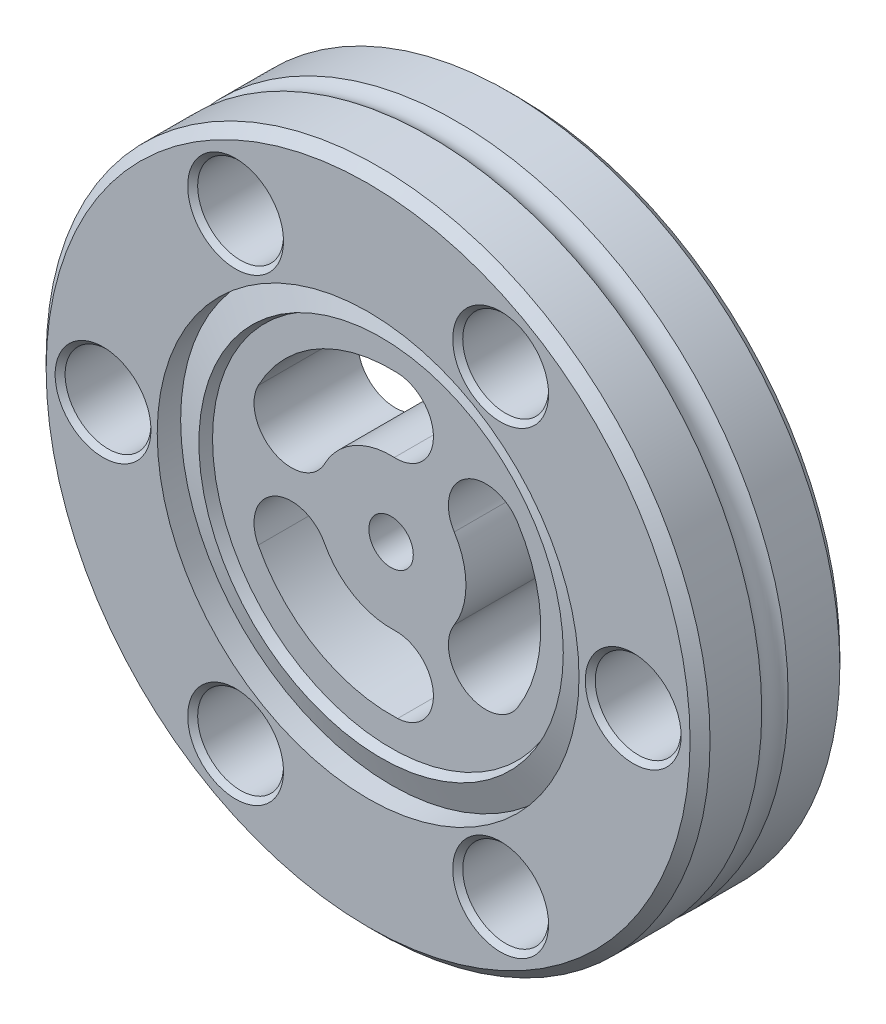
SolidWorks part; units mm, degrees
material "AISI 304"
ref_plane "Front Plane" through (0, 0, 0) normal (0, 0, 1) x (1, 0, 0)
ref_plane "Top Plane" through (0, 0, 0) normal (0, 1, 0) x (1, 0, 0)
ref_plane "Right Plane" through (0, 0, 0) normal (1, 0, 0) x (0, 0, -1)
sketch "Sketch1" plane through (0, 0, 0) normal (0, 1, 0) x (1, 0, 0)
  line L0 (9.0861, 2.6416) -> (0, 2.6416)
  line L1 (0, 2.6416) -> (0, -2.6416)
  line L2 (0, -2.6416) -> (9.0861, -2.6416)
  line L3 (9.0861, -2.6416) -> (9.271, -3.1496)
  line L4 (9.271, -3.1496) -> (10.7315, -2.618)
  line L5 (10.7315, -2.618) -> (10.7315, -3.81)
  line L6 (10.7315, -3.81) -> (16.891, -3.81)
  line L7 (16.891, -3.81) -> (16.891, -0.672)
  line L8 (16.891, 0.672) -> (16.891, 3.81)
  line L9 (16.891, 3.81) -> (10.7315, 3.81)
  line L10 (10.7315, 3.81) -> (10.7315, 2.618)
  line L11 (10.7315, 2.618) -> (9.271, 3.1496)
  line L12 (9.271, 3.1496) -> (9.0861, 2.6416)
  line L13 (0, 3.81) -> (0, -3.81) construction
  arc A0 (16.891, -0.672) -> (16.891, 0.672) centre (17.653, 0) cw
revolve "Revolve1" add sketch "Sketch1" angle 360 about L13
hole_wizard "M4 Clearance Hole1" positions "Sketch3" profile "Sketch2" hole size "M4" standard "ANSI Metric"
sketch "Sketch3" plane through (0, 0, -3.81) normal (0, 0, -1) x (-1, 0, 0)
  point P0 (6.7437, -11.6804)
  point P1 (6.7437, 11.6804)
  point P2 (-6.7437, 11.6804)
  point P3 (-13.4874, 0)
sketch "Sketch2" plane through (-6.7437, -11.6804, -3.81) normal (1, 0, 0) x (0, 1, 0)
  line L0 (0, 0) -> (0, 7.62)
  line L1 (0, 7.62) -> (2.1844, 7.62)
  line L2 (2.1844, 7.62) -> (2.1844, 0)
  line L5 (2.1844, 0) -> (0, 0)
  line L11 (0, -6.35) -> (0, 107.95) construction
  dimension "Thru Hole Dia." = 4.3688
  dimension "Thru Hole Depth" = 7.62
hole_wizard "M4 Clearance Hole2" positions "Sketch5" profile "Sketch4" hole size "M4" standard "ANSI Metric"
sketch "Sketch5" plane through (0, 0, 3.81) normal (0, 0, 1) x (1, 0, 0)
  point P0 (6.7437, -11.6804)
  point P1 (-13.4874, 0)
sketch "Sketch4" plane through (6.7437, -11.6804, 3.81) normal (1, 0, 0) x (0, -1, 0)
  line L0 (0, 0) -> (0, 7.62)
  line L1 (0, 7.62) -> (2.1844, 7.62)
  line L2 (2.1844, 7.62) -> (2.1844, 0)
  line L5 (2.1844, 0) -> (0, 0)
  line L11 (0, -6.35) -> (0, 107.95) construction
  dimension "Thru Hole Dia." = 4.3688
  dimension "Thru Hole Depth" = 7.62
chamfer "Chamfer1" distance 0.254 angle 45 12 edges at (-8.9281, 11.6804, 3.81) (-8.9281, -11.6804, 3.81) (8.9281, -11.6804, -3.81) (11.303, 0, 3.81) (-8.9281, -11.6804, -3.81) (8.9281, -11.6804, 3.81) (-11.303, 0, -3.81) (-11.303, 0, 3.81) (-8.9281, 11.6804, -3.81) (4.5593, 11.6804, 3.81) (4.5593, 11.6804, -3.81) (11.303, 0, -3.81)
chamfer "Chamfer2" distance 0.508 angle 45 2 edges at (16.891, 0, 3.81) (16.891, 0, -3.81)
hole_wizard "Tap Drill for #4-40 Tap1" positions "Sketch6" profile "Sketch7" hole size "#4-40" standard "ANSI Inch" end condition through all
sketch "Sketch6" plane through (0, 0, -2.6416) normal (0, 0, -1) x (-1, 0, 0)
  point P0 (0, 0)
sketch "Sketch7" plane through (0, 0, -2.6416) normal (1, 0, 0) x (0, 1, 0)
  line L0 (0, 0) -> (0, 6.4516)
  line L1 (0, 6.4516) -> (1.1303, 6.4516)
  line L2 (1.1303, 6.4516) -> (1.1303, 0)
  line L5 (1.1303, 0) -> (0, 0)
  line L11 (0, -6.35) -> (0, 107.95) construction
  dimension "Thru Hole Dia." = 2.2606
  dimension "Thru Hole Depth" = 6.4516
cosmetic thread "Cosmetic Thread1" parameters "D2"=2.8448
cosmetic thread "Cosmetic Thread2" parameters "D2"=2.8448
sketch "Sketch10" plane through (0, 0, 2.6416) normal (0, 0, 1) x (1, 0, 0)
  line L0 (0, 0) -> (22.3041, -14.2093) construction
  circle A0 centre (0, 0) radius 7.62 construction
  arc A1 (4.82, -3.0707) -> (4.82, 3.0707) centre (0, 0) ccw construction
  arc A2 (6.4266, -4.0942) -> (6.4266, 4.0942) centre (0, 0) ccw
  arc A3 (3.2133, -2.0471) -> (3.2133, 2.0471) centre (0, 0) ccw
  arc A4 (3.2133, -2.0471) -> (6.4266, -4.0942) centre (4.82, -3.0707) ccw
  arc A5 (6.4266, 4.0942) -> (3.2133, 2.0471) centre (4.82, 3.0707) ccw
  point P7 (5.715, 0)
  dimension "D1" = 3.81
  dimension "D3" = 5.715
  dimension "D2" = 65
extrude "Cut-Extrude1" cut sketch "Sketch10" against normal through all
pattern_circular "CirPattern1" count 3 over 360 about axis through (0, 0, 0) along (0, 0, 1) of "Cut-Extrude1"
